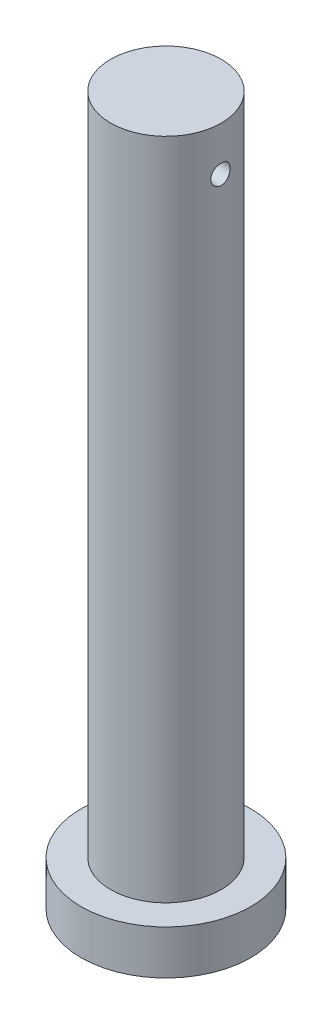
SolidWorks part; units mm, degrees
ref_plane "Front" through (0, 0, 0) normal (0, 0, 1) x (1, 0, 0)
ref_plane "Top" through (0, 0, 0) normal (0, 1, 0) x (1, 0, 0)
ref_plane "Right" through (0, 0, 0) normal (1, 0, 0) x (0, 0, -1)
sketch "Sketch1" plane through (0, 0, 0) normal (0, 1, 0) x (1, 0, 0)
  circle A0 centre (0, 0) radius 23
  dimension "D1" = 46
extrude "Boss-Extrude1" add sketch "Sketch1" along normal blind 12
sketch "Sketch2" plane through (0, 12, 0) normal (0, 1, 0) x (1, 0, 0)
  circle A0 centre (0, 0) radius 15
  dimension "D1" = 30
extrude "Boss-Extrude2" add sketch "Sketch2" along normal blind 180
ref_plane "Plane2" through (0, 180, 0) normal (0, 1, 0) x (1, 0, 0)
sketch "Sketch4" plane through (0, 180, 0) normal (0, 1, 0) x (1, 0, 0)
  line L0 (30, 0) -> (-30, 0)
  line L1 (-30, 0) -> (-30, 3)
  line L2 (-30, 3) -> (30, 2.5)
  line L3 (30, 2.5) -> (30, 0)
  point P6 (0, 0)
  dimension "D1" = 60
  dimension "D2" = 3
  dimension "D3" = 2.5
revolve "Cut-Revolve4" cut sketch "Sketch4" angle 360 about L0
scale "Scale1" scale about centroid uniform scaling yes scale factor 0.33
